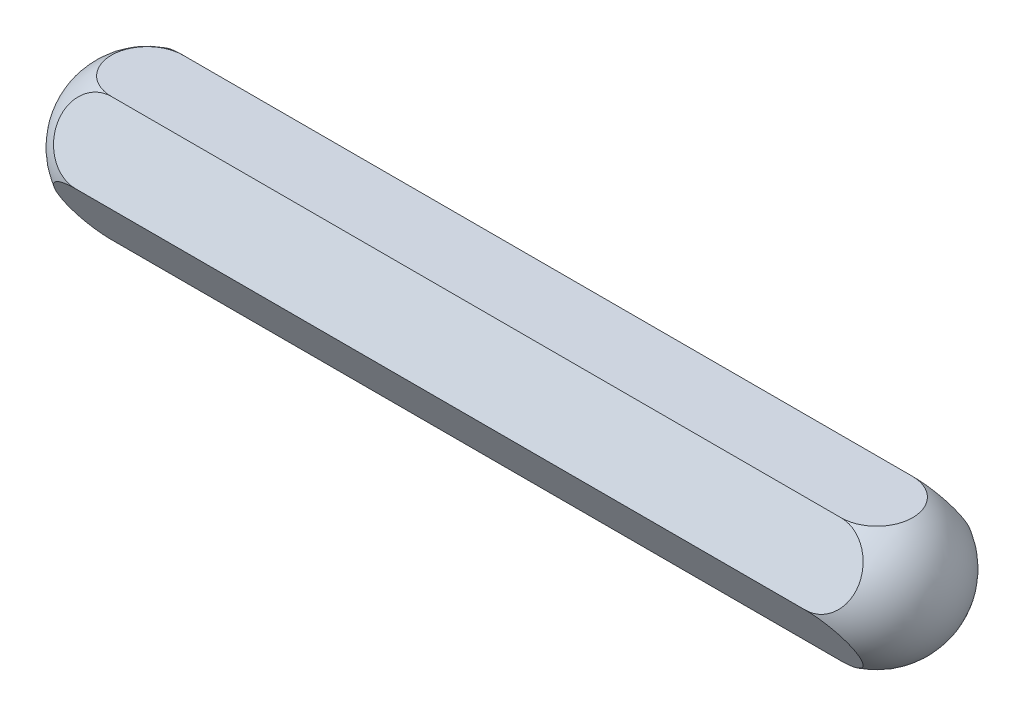
SolidWorks part; units mm, degrees
ref_plane "Front Plane" through (0, 0, 0) normal (0, 0, 1) x (1, 0, 0)
ref_plane "Top Plane" through (0, 0, 0) normal (0, 1, 0) x (1, 0, 0)
ref_plane "Right Plane" through (0, 0, 0) normal (1, 0, 0) x (0, 0, -1)
sketch "Sketch1" plane through (0, 0, 0) normal (0, 0, 1) x (1, 0, 0)
  line L0 (-21.4, 4.2) -> (21.4, 4.2)
  line L3 (-25.6, 0) -> (25.6, 0)
  arc A0 (-21.4, 4.2) -> (-25.6, 0) centre (-21.4, 0) ccw
  arc A1 (21.4, 4.2) -> (25.6, 0) centre (21.4, 0) cw
  point P2 (0, 0)
  point P5 (-13.7501, 0)
  point P6 (0, 0)
  dimension "D1" = 4.2
  dimension "D2" = 51.2
revolve "Body Revolve" add sketch "Sketch1" angle 360 about L3
sketch "Sketch2" plane through (0, 0, 0) normal (1, 0, 0) x (0, 0, -1)
  line L1 (-2.1, 3.6373) -> (-4.2, 0)
  line L2 (-4.2, 0) -> (-2.1, -3.6373)
  line L3 (-2.1, -3.6373) -> (2.1, -3.6373)
  line L4 (2.1, -3.6373) -> (4.2, 0)
  line L5 (4.2, 0) -> (2.1, 3.6373)
  line L6 (2.1, 3.6373) -> (-2.1, 3.6373)
  circle A0 centre (0, 0) radius 4.2 construction
  circle A1 centre (0, 0) radius 4.2
  circle A2 centre (0, 0) radius 3.6373 construction
  point P3 (-2.4156, 4.2)
  point P11 (-1.6816, 2.9126)
  point P12 (0, 0)
extrude "Octagonal Cut" cut sketch "Sketch2" against normal through all both and the other way through all contours L1 A1 | L6 A1 | L5 A1 | L4 A1 | L3 A1 | L2 A1
